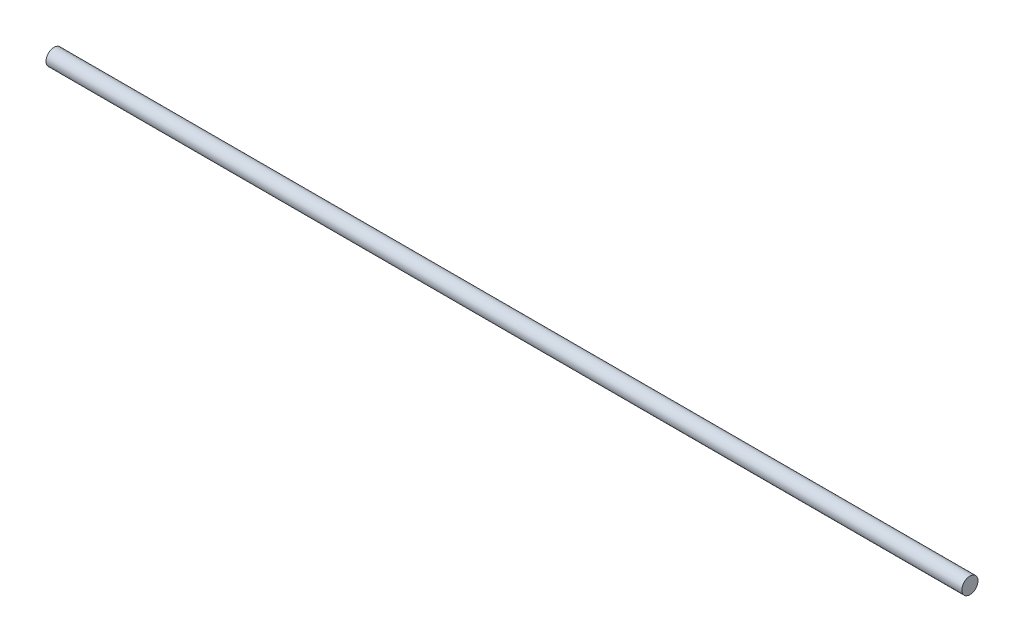
SolidWorks part; units mm, degrees
ref_plane "Front Plane" through (0, 0, 0) normal (0, 0, 1) x (1, 0, 0)
ref_plane "Top Plane" through (0, 0, 0) normal (0, 1, 0) x (1, 0, 0)
ref_plane "Right Plane" through (0, 0, 0) normal (1, 0, 0) x (0, 0, -1)
sketch "Sketch3" plane through (0, 0, 0) normal (1, 0, 0) x (0, 0, -1)
  circle A0 centre (0, 0) radius 19.05
  dimension "D1" = 38.1
extrude "Boss-Extrude1" add sketch "Sketch3" along normal blind 2159
